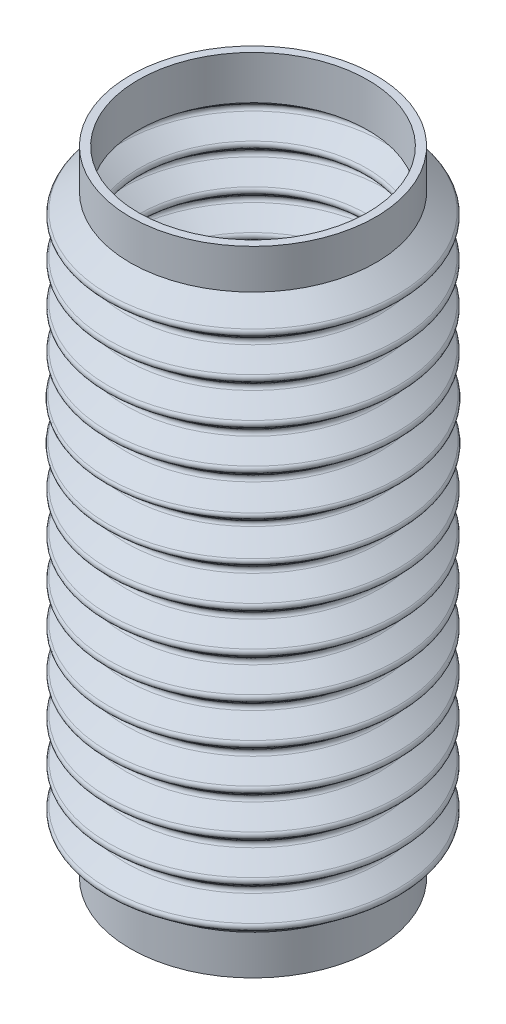
SolidWorks part; units mm, degrees
material "Амортизационная резина"
ref_plane "Front Plane" through (0, 0, 0) normal (0, 0, 1) x (1, 0, 0)
ref_plane "Top Plane" through (0, 0, 0) normal (0, 1, 0) x (1, 0, 0)
ref_plane "Right Plane" through (0, 0, 0) normal (1, 0, 0) x (0, 0, -1)
sketch "Sketch1" plane through (0, 0, 0) normal (1, 0, 0) x (0, 0, -1)
  line L0 (0, 63.2576) -> (0, -132.6391) construction
  line L1 (-31, 31.1234) -> (-31, 21.1234)
  line L2 (-34.2198, -113.8766) -> (-29, -117.8918) construction
  line L3 (-31, 21.1234) -> (-36.4696, 16.916)
  line L4 (-27.7198, -108.8766) -> (-34.2198, -113.8766) construction
  line L5 (-36.4696, 15.3308) -> (-32.0304, 11.916)
  line L6 (-37.5, -113.8766) -> (-31, -118.8766) construction
  line L7 (-32.0304, 10.3308) -> (-36.4696, 6.916)
  line L8 (-31, -108.8766) -> (-37.5, -113.8766) construction
  line L9 (-36.4696, 5.3308) -> (-32.0304, 1.916)
  line L10 (-34.2198, -103.8766) -> (-27.7198, -108.8766) construction
  line L11 (-29, 31.1234) -> (-29, 20.1386)
  line L12 (-29, 20.1386) -> (-33.1893, 16.916)
  line L13 (-37.5, -103.8766) -> (-31, -108.8766) construction
  line L14 (-32.0304, 0.3308) -> (-36.4696, -3.084)
  line L15 (-36.4696, -4.6692) -> (-32.0304, -8.084)
  line L16 (-32.0304, -9.6692) -> (-36.4696, -13.084)
  line L17 (-36.4696, -14.6692) -> (-32.0304, -18.084)
  line L18 (-32.0304, -19.6692) -> (-36.6331, -23.2097)
  line L19 (-36.6331, -24.5435) -> (-31.8669, -28.2097)
  line L20 (-31.8669, -29.5435) -> (-36.6331, -33.2097)
  line L21 (-36.6331, -34.5435) -> (-32.0304, -38.084)
  line L22 (-32.0304, -39.6692) -> (-36.4696, -43.084)
  line L23 (-36.4696, -44.6692) -> (-32.0304, -48.084)
  line L24 (-32.0304, -49.6692) -> (-36.4696, -53.084)
  line L25 (-36.4696, -54.6692) -> (-32.0304, -58.084)
  line L26 (-32.0304, -59.6692) -> (-36.4696, -63.084)
  line L27 (-36.4696, -64.6692) -> (-32.0304, -68.084)
  line L28 (-32.0304, -69.6692) -> (-36.4696, -73.084)
  line L29 (-36.4696, -74.6692) -> (-32.0304, -78.084)
  line L30 (-32.0304, -79.6692) -> (-36.4696, -83.084)
  line L31 (-36.4696, -84.6692) -> (-32.0304, -88.084)
  line L32 (-32.0304, -89.6692) -> (-36.4696, -93.084)
  line L33 (-36.4696, -94.6692) -> (-32.0304, -98.084)
  line L34 (-32.0304, -99.6692) -> (-36.4696, -103.084)
  line L35 (-36.4696, -104.6692) -> (-32.0304, -108.084)
  line L36 (-32.0304, -109.6692) -> (-36.4696, -113.084)
  line L37 (-36.4696, -114.6692) -> (-31, -118.8766)
  line L38 (-27.7198, -98.8766) -> (-34.2198, -103.8766) construction
  line L39 (-31, -98.8766) -> (-37.5, -103.8766) construction
  line L40 (-34.2198, -93.8766) -> (-27.7198, -98.8766) construction
  line L41 (-37.5, -93.8766) -> (-31, -98.8766) construction
  line L42 (-27.7198, -88.8766) -> (-34.2198, -93.8766) construction
  line L43 (-31, -88.8766) -> (-37.5, -93.8766) construction
  line L44 (-34.2198, -83.8766) -> (-27.7198, -88.8766) construction
  line L45 (-37.5, -83.8766) -> (-31, -88.8766) construction
  line L46 (-27.7198, -78.8766) -> (-34.2198, -83.8766) construction
  line L47 (-31, -78.8766) -> (-37.5, -83.8766) construction
  line L48 (-34.2198, -73.8766) -> (-27.7198, -78.8766) construction
  line L49 (-37.5, -73.8766) -> (-31, -78.8766) construction
  line L50 (-27.7198, -68.8766) -> (-34.2198, -73.8766) construction
  line L51 (-31, -68.8766) -> (-37.5, -73.8766) construction
  line L52 (-34.2198, -63.8766) -> (-27.7198, -68.8766) construction
  line L53 (-37.5, -63.8766) -> (-31, -68.8766) construction
  line L54 (-27.7198, -58.8766) -> (-34.2198, -63.8766) construction
  line L55 (-31, -58.8766) -> (-37.5, -63.8766) construction
  line L56 (-34.2198, -53.8766) -> (-27.7198, -58.8766) construction
  line L57 (-37.5, -53.8766) -> (-31, -58.8766) construction
  line L58 (-27.7198, -48.8766) -> (-34.2198, -53.8766) construction
  line L59 (-31, -48.8766) -> (-37.5, -53.8766) construction
  line L60 (-34.2198, -43.8766) -> (-27.7198, -48.8766) construction
  line L61 (-37.5, -43.8766) -> (-31, -48.8766) construction
  line L62 (-31, -118.8766) -> (-31, -128.8766)
  line L63 (-27.7198, -38.8766) -> (-34.2198, -43.8766) construction
  line L64 (-33.1893, 15.3308) -> (-28.7502, 11.916)
  line L65 (-28.7502, 10.3308) -> (-33.1893, 6.916)
  line L66 (-33.1893, 5.3308) -> (-28.7502, 1.916)
  line L67 (-28.7502, 0.3308) -> (-33.1893, -3.084)
  line L68 (-33.1893, -4.6692) -> (-28.7502, -8.084)
  line L69 (-28.7502, -9.6692) -> (-33.1893, -13.084)
  line L70 (-33.1893, -14.6692) -> (-28.7502, -18.084)
  line L71 (-28.7502, -19.6692) -> (-33.3528, -23.2097)
  line L72 (-33.3528, -24.5435) -> (-28.5867, -28.2097)
  line L73 (-28.5867, -29.5435) -> (-33.3528, -33.2097)
  line L74 (-33.3528, -34.5435) -> (-28.7502, -38.084)
  line L75 (-28.7502, -39.6692) -> (-33.1893, -43.084)
  line L76 (-33.1893, -44.6692) -> (-28.7502, -48.084)
  line L77 (-28.7502, -49.6692) -> (-33.1893, -53.084)
  line L78 (-33.1893, -54.6692) -> (-28.7502, -58.084)
  line L79 (-28.7502, -59.6692) -> (-33.1893, -63.084)
  line L80 (-33.1893, -64.6692) -> (-28.7502, -68.084)
  line L81 (-28.7502, -69.6692) -> (-33.1893, -73.084)
  line L82 (-33.1893, -74.6692) -> (-28.7502, -78.084)
  line L83 (-28.7502, -79.6692) -> (-33.1893, -83.084)
  line L84 (-33.1893, -84.6692) -> (-28.7502, -88.084)
  line L85 (-28.7502, -89.6692) -> (-33.1893, -93.084)
  line L86 (-33.1893, -94.6692) -> (-28.7502, -98.084)
  line L87 (-28.7502, -99.6692) -> (-33.1893, -103.084)
  line L88 (-33.1893, -104.6692) -> (-28.7502, -108.084)
  line L89 (-28.7502, -109.6692) -> (-33.1893, -113.084)
  line L90 (-33.1893, -114.6692) -> (-29, -117.8918)
  line L91 (-29, -117.8918) -> (-29, -128.8766)
  line L92 (-29, 31.1234) -> (-31, 31.1234)
  line L93 (-29, -128.8766) -> (-31, -128.8766)
  line L94 (-31, -38.8766) -> (-37.5, -43.8766) construction
  line L95 (-34.2198, -33.8766) -> (-27.7198, -38.8766) construction
  line L96 (-37.5, -33.8766) -> (-31, -38.8766) construction
  line L97 (-34.2198, 16.1234) -> (-27.7198, 11.1234) construction
  line L98 (-29, 20.1386) -> (-34.2198, 16.1234) construction
  line L99 (-37.5, 16.1234) -> (-31, 11.1234) construction
  line L100 (-31, 21.1234) -> (-37.5, 16.1234) construction
  line L101 (-34.2198, 6.1234) -> (-27.7198, 1.1234) construction
  line L102 (-27.7198, 11.1234) -> (-34.2198, 6.1234) construction
  line L103 (-37.5, 6.1234) -> (-31, 1.1234) construction
  line L104 (-31, 11.1234) -> (-37.5, 6.1234) construction
  line L105 (-37.5, -3.8766) -> (-31, -8.8766) construction
  line L106 (-31, 1.1234) -> (-37.5, -3.8766) construction
  line L107 (-27.7198, 1.1234) -> (-34.2198, -3.8766) construction
  line L108 (-34.2198, -3.8766) -> (-27.7198, -8.8766) construction
  line L109 (-27.7198, -8.8766) -> (-34.2198, -13.8766) construction
  line L110 (-31, -8.8766) -> (-37.5, -13.8766) construction
  line L111 (-27.7198, -18.8766) -> (-34.2198, -23.8766) construction
  line L112 (-34.2198, -13.8766) -> (-27.7198, -18.8766) construction
  line L113 (-31, -18.8766) -> (-37.5, -23.8766) construction
  line L114 (-37.5, -13.8766) -> (-31, -18.8766) construction
  line L115 (-27.7198, -28.8766) -> (-34.2198, -33.8766) construction
  line L116 (-31, -28.8766) -> (-37.5, -33.8766) construction
  line L117 (-34.2198, -23.8766) -> (-27.7198, -28.8766) construction
  line L118 (-37.5, -23.8766) -> (-31, -28.8766) construction
  arc A0 (-33.1893, -114.6692) -> (-33.1893, -113.084) centre (-32.5796, -113.8766) cw
  arc A1 (-36.4696, -114.6692) -> (-36.4696, -113.084) centre (-35.8599, -113.8766) cw
  arc A2 (-28.7502, -109.6692) -> (-28.7502, -108.084) centre (-29.3599, -108.8766) ccw
  arc A3 (-32.0304, -109.6692) -> (-32.0304, -108.084) centre (-32.6401, -108.8766) ccw
  arc A4 (-33.1893, -104.6692) -> (-33.1893, -103.084) centre (-32.5796, -103.8766) cw
  arc A5 (-36.4696, -104.6692) -> (-36.4696, -103.084) centre (-35.8599, -103.8766) cw
  arc A6 (-28.7502, -99.6692) -> (-28.7502, -98.084) centre (-29.3599, -98.8766) ccw
  arc A7 (-32.0304, -99.6692) -> (-32.0304, -98.084) centre (-32.6401, -98.8766) ccw
  arc A8 (-33.1893, -94.6692) -> (-33.1893, -93.084) centre (-32.5796, -93.8766) cw
  arc A9 (-36.4696, -94.6692) -> (-36.4696, -93.084) centre (-35.8599, -93.8766) cw
  arc A10 (-28.7502, -89.6692) -> (-28.7502, -88.084) centre (-29.3599, -88.8766) ccw
  arc A11 (-32.0304, -89.6692) -> (-32.0304, -88.084) centre (-32.6401, -88.8766) ccw
  arc A12 (-33.1893, -84.6692) -> (-33.1893, -83.084) centre (-32.5796, -83.8766) cw
  arc A13 (-36.4696, -84.6692) -> (-36.4696, -83.084) centre (-35.8599, -83.8766) cw
  arc A14 (-28.7502, -79.6692) -> (-28.7502, -78.084) centre (-29.3599, -78.8766) ccw
  arc A15 (-32.0304, -79.6692) -> (-32.0304, -78.084) centre (-32.6401, -78.8766) ccw
  arc A16 (-33.1893, -74.6692) -> (-33.1893, -73.084) centre (-32.5796, -73.8766) cw
  arc A17 (-36.4696, -74.6692) -> (-36.4696, -73.084) centre (-35.8599, -73.8766) cw
  arc A18 (-28.7502, -69.6692) -> (-28.7502, -68.084) centre (-29.3599, -68.8766) ccw
  arc A19 (-32.0304, -69.6692) -> (-32.0304, -68.084) centre (-32.6401, -68.8766) ccw
  arc A20 (-33.1893, -64.6692) -> (-33.1893, -63.084) centre (-32.5796, -63.8766) cw
  arc A21 (-36.4696, -64.6692) -> (-36.4696, -63.084) centre (-35.8599, -63.8766) cw
  arc A22 (-28.7502, -59.6692) -> (-28.7502, -58.084) centre (-29.3599, -58.8766) ccw
  arc A23 (-32.0304, -59.6692) -> (-32.0304, -58.084) centre (-32.6401, -58.8766) ccw
  arc A24 (-33.1893, -54.6692) -> (-33.1893, -53.084) centre (-32.5796, -53.8766) cw
  arc A25 (-36.4696, -54.6692) -> (-36.4696, -53.084) centre (-35.8599, -53.8766) cw
  arc A26 (-28.7502, -48.084) -> (-28.7502, -49.6692) centre (-29.3599, -48.8766) cw
  arc A27 (-32.0304, -48.084) -> (-32.0304, -49.6692) centre (-32.6401, -48.8766) cw
  arc A28 (-33.1893, -44.6692) -> (-33.1893, -43.084) centre (-32.5796, -43.8766) cw
  arc A29 (-36.4696, -44.6692) -> (-36.4696, -43.084) centre (-35.8599, -43.8766) cw
  arc A30 (-28.7502, -39.6692) -> (-28.7502, -38.084) centre (-29.3599, -38.8766) ccw
  arc A31 (-32.0304, -39.6692) -> (-32.0304, -38.084) centre (-32.6401, -38.8766) ccw
  arc A32 (-33.1893, 15.3308) -> (-33.1893, 16.916) centre (-32.5796, 16.1234) cw
  arc A33 (-36.4696, 15.3308) -> (-36.4696, 16.916) centre (-35.8599, 16.1234) cw
  arc A34 (-33.1893, 5.3308) -> (-33.1893, 6.916) centre (-32.5796, 6.1234) cw
  arc A35 (-36.4696, 5.3308) -> (-36.4696, 6.916) centre (-35.8599, 6.1234) cw
  arc A36 (-28.7502, 10.3308) -> (-28.7502, 11.916) centre (-29.3599, 11.1234) ccw
  arc A37 (-32.0304, 10.3308) -> (-32.0304, 11.916) centre (-32.6401, 11.1234) ccw
  arc A38 (-36.4696, -4.6692) -> (-36.4696, -3.084) centre (-35.8599, -3.8766) cw
  arc A39 (-28.7502, 1.916) -> (-28.7502, 0.3308) centre (-29.3599, 1.1234) cw
  arc A40 (-32.0304, 1.916) -> (-32.0304, 0.3308) centre (-32.6401, 1.1234) cw
  arc A41 (-28.7502, -8.084) -> (-28.7502, -9.6692) centre (-29.3599, -8.8766) cw
  arc A42 (-32.0304, -8.084) -> (-32.0304, -9.6692) centre (-32.6401, -8.8766) cw
  arc A43 (-33.1893, -3.084) -> (-33.1893, -4.6692) centre (-32.5796, -3.8766) ccw
  arc A44 (-28.7502, -19.6692) -> (-28.7502, -18.084) centre (-29.3599, -18.8766) ccw
  arc A45 (-32.0304, -19.6692) -> (-32.0304, -18.084) centre (-32.6401, -18.8766) ccw
  arc A46 (-33.1893, -14.6692) -> (-33.1893, -13.084) centre (-32.5796, -13.8766) cw
  arc A47 (-36.4696, -14.6692) -> (-36.4696, -13.084) centre (-35.8599, -13.8766) cw
  arc A48 (-33.3528, -34.5435) -> (-33.3528, -33.2097) centre (-32.8399, -33.8766) cw
  arc A49 (-36.6331, -34.5435) -> (-36.6331, -33.2097) centre (-36.1201, -33.8766) cw
  arc A50 (-28.5867, -29.5435) -> (-28.5867, -28.2097) centre (-29.0997, -28.8766) ccw
  arc A51 (-31.8669, -29.5435) -> (-31.8669, -28.2097) centre (-32.3799, -28.8766) ccw
  arc A52 (-33.3528, -24.5435) -> (-33.3528, -23.2097) centre (-32.8399, -23.8766) cw
  arc A53 (-36.6331, -24.5435) -> (-36.6331, -23.2097) centre (-36.1201, -23.8766) cw
  dimension "D1" = 1
  dimension "D2" = 1
  dimension "D6" = 1
  dimension "D7" = 1
  dimension "D3" = 1
  dimension "D4" = 1
  dimension "D10" = 1
  dimension "D11" = 0.8413
  dimension "D8" = 10
  dimension "D12" = 58
  dimension "D13" = 58
  dimension "D9" = 2
  dimension "D5" = 13
revolve "Revolve1" add sketch "Sketch1" angle 360 about L0
